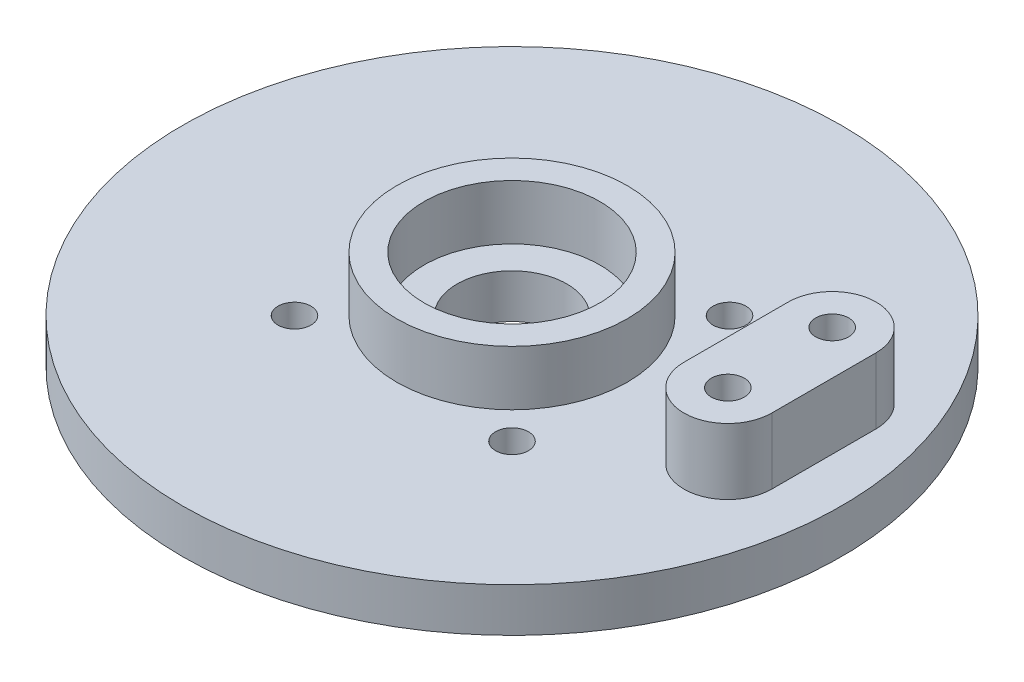
SolidWorks part; units mm, degrees
ref_plane "Alzado" through (0, 0, 0) normal (0, 0, 1) x (1, 0, 0)
ref_plane "Planta" through (0, 0, 0) normal (0, 1, 0) x (1, 0, 0)
ref_plane "Vista lateral" through (0, 0, 0) normal (1, 0, 0) x (0, 0, -1)
sketch "Croquis1" plane through (0, 0, 0) normal (0, 1, 0) x (1, 0, 0)
  circle A0 centre (0, 0) radius 30
  dimension "D1" = 60
extrude "Saliente-Extruir1" add sketch "Croquis1" along normal blind 4
sketch "Croquis2" plane through (0, 4, 0) normal (0, 1, 0) x (1, 0, 0)
  circle A0 centre (0, 0) radius 10.5
  circle A1 centre (0, 0) radius 8
  dimension "D1" = 21
  dimension "D2" = 16
extrude "Saliente-Extruir2" add sketch "Croquis2" along normal blind 5
sketch "Croquis4" plane through (0, 4, 0) normal (0, 1, 0) x (1, 0, 0)
  circle A0 centre (0, 0) radius 5
  circle A1 centre (-9.9, 9.9) radius 1.5
  circle A2 centre (9.9, 9.9) radius 1.5
  circle A3 centre (9.9, -9.9) radius 1.5
  circle A4 centre (-9.9, -9.9) radius 1.5
  dimension "D1" = 10
  dimension "D4" = 3
  dimension "D2" = 19.8
  dimension "D3" = 19.8
extrude "Cortar-Extruir1" cut sketch "Croquis4" against normal through all
sketch "Croquis5" plane through (0, 4, 0) normal (0, 1, 0) x (1, 0, 0)
  line L0 (21.5, -1.8535) -> (21.5, 7.6465) construction
  line L1 (17.5, -1.8535) -> (17.5, 7.6465)
  line L2 (25.5, -1.8535) -> (25.5, 7.6465)
  line L3 (0, 0) -> (17.5, 0) construction
  line L4 (29.9996, 0.1468) -> (25.5, 7.6465) construction
  line L5 (25.5, -1.8535) -> (29.9996, 0.1468) construction
  arc A0 (17.5, -1.8535) -> (25.5, -1.8535) centre (21.5, -1.8535) ccw
  arc A1 (25.5, 7.6465) -> (17.5, 7.6465) centre (21.5, 7.6465) ccw
  circle A2 centre (21.5, 7.6465) radius 1.5
  circle A3 centre (21.5, -1.8535) radius 1.5
  circle A4 centre (0, 0) radius 30 construction
  point P2 (21.5, 2.8965)
  dimension "D2" = 4
  dimension "D3" = 3
  dimension "D5" = 8.746
  dimension "D1" = 9.5
  dimension "D4" = 17.5
extrude "Saliente-Extruir3" add sketch "Croquis5" along normal blind 6
sketch "Croquis6" plane through (0, 10, 0) normal (0, 1, 0) x (1, 0, 0)
  circle A0 centre (21.5, 7.6465) radius 1.5
  circle A1 centre (21.5, -1.8535) radius 1.5
extrude "Cortar-Extruir4" cut sketch "Croquis6" against normal through all
